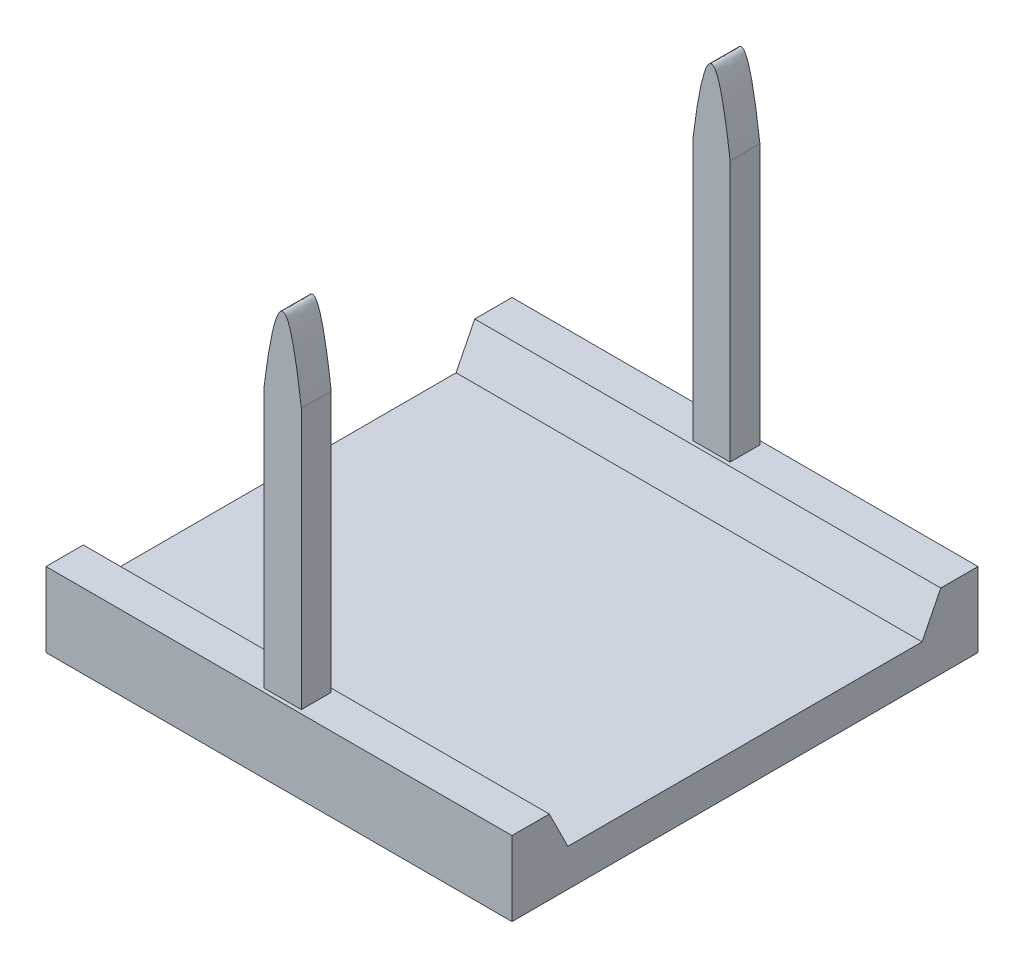
SolidWorks part; units mm, degrees
ref_plane "Front Plane" through (0, 0, 0) normal (0, 0, 1) x (1, 0, 0)
ref_plane "Top Plane" through (0, 0, 0) normal (0, 1, 0) x (1, 0, 0)
ref_plane "Right Plane" through (0, 0, 0) normal (1, 0, 0) x (0, 0, -1)
sketch "Sketch2" plane through (0, 0, 0) normal (0, 1, 0) x (1, 0, 0)
  line L1 (0, 0) -> (125, 0)
  line L2 (0, 0) -> (0, 125)
  line L3 (0, 125) -> (125, 125)
  line L4 (125, 0) -> (125, 125)
  line L5 (0, 0) -> (125, 125) construction
  line L6 (0, 125) -> (125, 0) construction
  point P4 (62.5, 62.5)
  dimension "D1" = 125
  dimension "D2" = 125
extrude "Boss-Extrude1" add sketch "Sketch2" along normal blind 20
sketch "Sketch4" plane through (125, 0, 0) normal (1, 0, 0) x (0, 0, -1)
  line L0 (10, 20) -> (15, 10)
  line L1 (0, 20) -> (125, 20) construction
  line L2 (15, 10) -> (110, 10)
  line L3 (110, 10) -> (115, 20)
  line L4 (0, 20) -> (0, 0) construction
  dimension "D1" = 10
  dimension "D2" = 10
  dimension "D3" = 95
  dimension "D4" = 10
  dimension "D5" = 5
extrude "Cut-Extrude1" cut sketch "Sketch4" against normal through all and the other way through all
sketch "Sketch3" plane through (0, 0, 0) normal (0, 0, 1) x (1, 0, 0)
  line L0 (57.5, 20) -> (57.5, 90)
  line L1 (0, 20) -> (125, 20) construction
  line L2 (67.5, 20) -> (67.5, 90)
  line L3 (0, 20) -> (0, 0) construction
  line L5 (57.5, 20) -> (67.5, 20)
  spline S0 degree 2 poles (57.5, 90) (62.5, 130) (67.5, 90) knots 0 0 0 1 1 1
  dimension "D1" = 10
  dimension "D2" = 57.5
  dimension "D3" = 5
  dimension "D4" = 70
  dimension "D5" = 20
extrude "Boss-Extrude2" add sketch "Sketch3" against normal blind 10
sketch "Sketch6" plane through (0, 0, 0) normal (0, 0, 1) x (1, 0, 0)
  line L0 (57.5, 20) -> (67.5, 20)
  line L7 (0, 0) -> (125, 0)
  line L8 (125, 0) -> (125, 20)
  line L9 (125, 20) -> (67.5, 20)
  line L10 (67.5, 20) -> (67.5, 90)
  line L11 (57.5, 90) -> (57.5, 20)
  line L12 (57.5, 20) -> (0, 20)
  line L13 (0, 20) -> (0, 0)
  line L17 (67.5, 20) -> (67.5, 90)
  line L18 (57.5, 90) -> (57.5, 20)
  parabola Q1 (67.5, 90) -> (57.5, 90) focus (62.5, 109.6875) apex (62.5, 110)
  parabola Q2 (67.5, 90) -> (57.5, 90) focus (62.5, 109.6875) apex (62.5, 110)
  dimension "D1" = 0
extrude "Cut-Extrude2" cut sketch "Sketch6" against normal blind 1
sketch "Sketch7" plane through (0, 0, -10) normal (0, 0, -1) x (-1, 0, 0)
  line L3 (-67.5, 20) -> (-57.5, 20)
  line L4 (-57.5, 20) -> (-57.5, 90)
  line L5 (-67.5, 90) -> (-67.5, 20)
  line L6 (-67.5, 20) -> (-57.5, 20)
  line L7 (-57.5, 20) -> (-57.5, 90)
  line L8 (-67.5, 90) -> (-67.5, 20)
  parabola Q1 (-57.5, 90) -> (-67.5, 90) focus (-62.5, 109.6875) apex (-62.5, 110)
  parabola Q2 (-57.5, 90) -> (-67.5, 90) focus (-62.5, 109.6875) apex (-62.5, 110)
  dimension "D1" = 0
extrude "Cut-Extrude3" cut sketch "Sketch7" against normal blind 1
ref_plane "Plane1" through (0, 0, -62.5) normal (0, 0, 1) x (1, 0, 0)
mirror "Mirror1" about plane through (0, 0, -62.5) normal (0, 0, 1) of "Boss-Extrude2", "Cut-Extrude2", "Cut-Extrude3"
